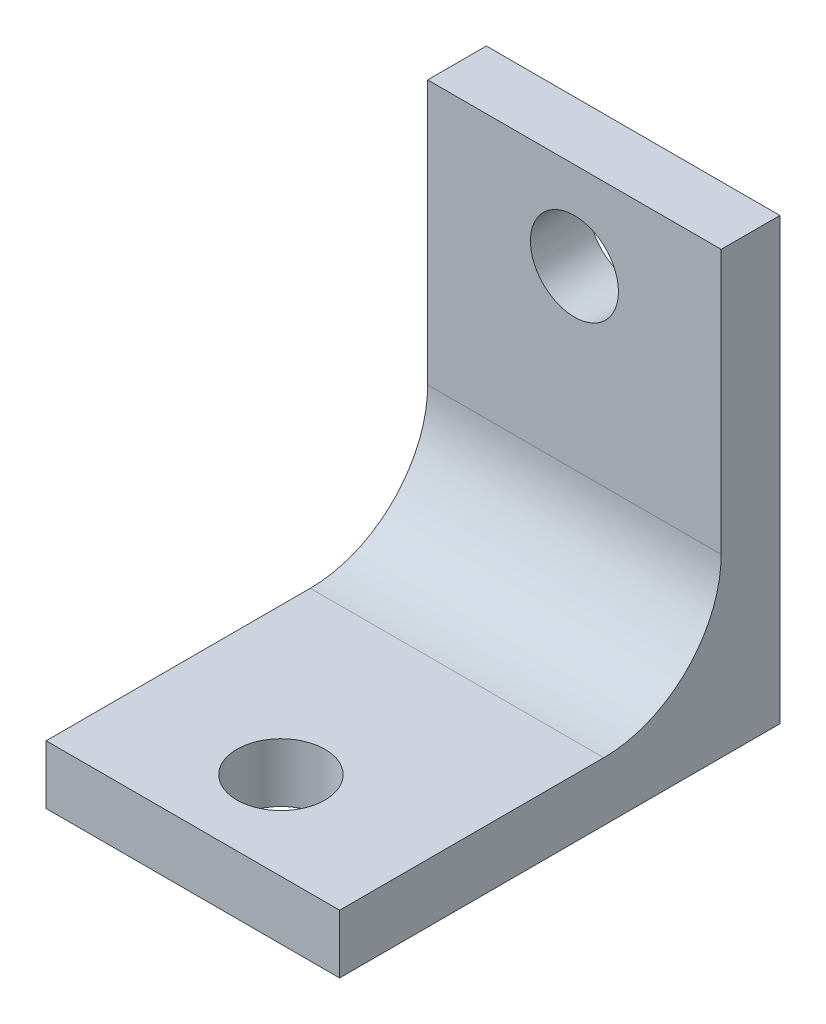
SolidWorks part; units mm, degrees
material "6061 Alloy"
ref_plane "Front Plane" through (0, 0, 0) normal (0, 0, 1) x (1, 0, 0)
ref_plane "Top Plane" through (0, 0, 0) normal (0, 1, 0) x (1, 0, 0)
ref_plane "Right Plane" through (0, 0, 0) normal (1, 0, 0) x (0, 0, -1)
sketch "Sketch1" plane through (0, 0, 0) normal (1, 0, 0) x (0, 0, -1)
  line L0 (0, 0) -> (0, 15)
  line L1 (0, 15) -> (-2, 15)
  line L2 (-2, 15) -> (-2, 2)
  line L3 (-2, 2) -> (-15, 2)
  line L4 (-15, 2) -> (-15, 0)
  line L5 (-15, 0) -> (0, 0)
  dimension "D1" = 2
  dimension "D2" = 2
  dimension "D3" = 15
  dimension "D4" = 15
extrude "Boss-Extrude1" add sketch "Sketch1" along normal blind 10
sketch "Sketch2" plane through (0, 0, 2) normal (0, 0, 1) x (1, 0, 0)
  line L0 (10, 15) -> (0, 15) construction
  circle A0 centre (5, 12) radius 1.5
  point P5 (5, 15)
  dimension "D1" = 3
  dimension "D2" = 3
extrude "Cut-Extrude1" cut sketch "Sketch2" against normal blind 10
sketch "Sketch3" plane through (0, 2, 0) normal (0, 1, 0) x (1, 0, 0)
  line L0 (10, -15) -> (0, -15) construction
  circle A0 centre (5, -12) radius 1.5
  point P5 (5, -15)
  dimension "D1" = 3
  dimension "D2" = 3
extrude "Cut-Extrude2" cut sketch "Sketch3" against normal blind 10
fillet "Fillet1" radius 4 1 edges at (5, 2, 2)
